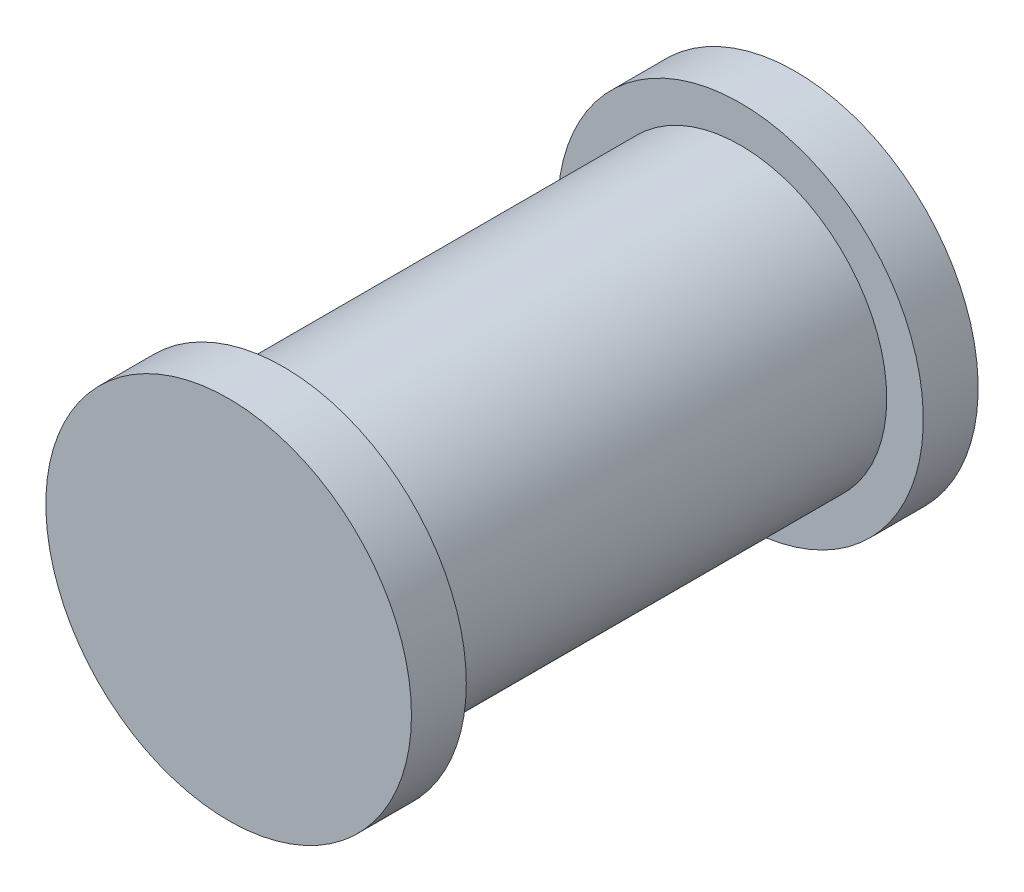
SolidWorks part; units mm, degrees
ref_plane "前视基准面" through (0, 0, 0) normal (0, 0, 1) x (1, 0, 0)
ref_plane "上视基准面" through (0, 0, 0) normal (0, 1, 0) x (1, 0, 0)
ref_plane "右视基准面" through (0, 0, 0) normal (1, 0, 0) x (0, 0, -1)
other "Configuration Table"
sketch "草图1" plane through (0, 0, 0) normal (0, 0, 1) x (1, 0, 0)
  circle A0 centre (0, 0) radius 8
extrude "凸台-拉伸3" add sketch "草图1" along normal blind 25
sketch "草图3" plane through (0, 0, 25) normal (0, 0, 1) x (1, 0, 0)
  circle A0 centre (0, 0) radius 10
extrude "凸台-拉伸4" add sketch "草图3" along normal blind 3
sketch "草图4" plane through (0, 0, 0) normal (0, 0, -1) x (-1, 0, 0)
  circle A0 centre (0, 0) radius 10
extrude "凸台-拉伸5" add sketch "草图4" along normal blind 3
